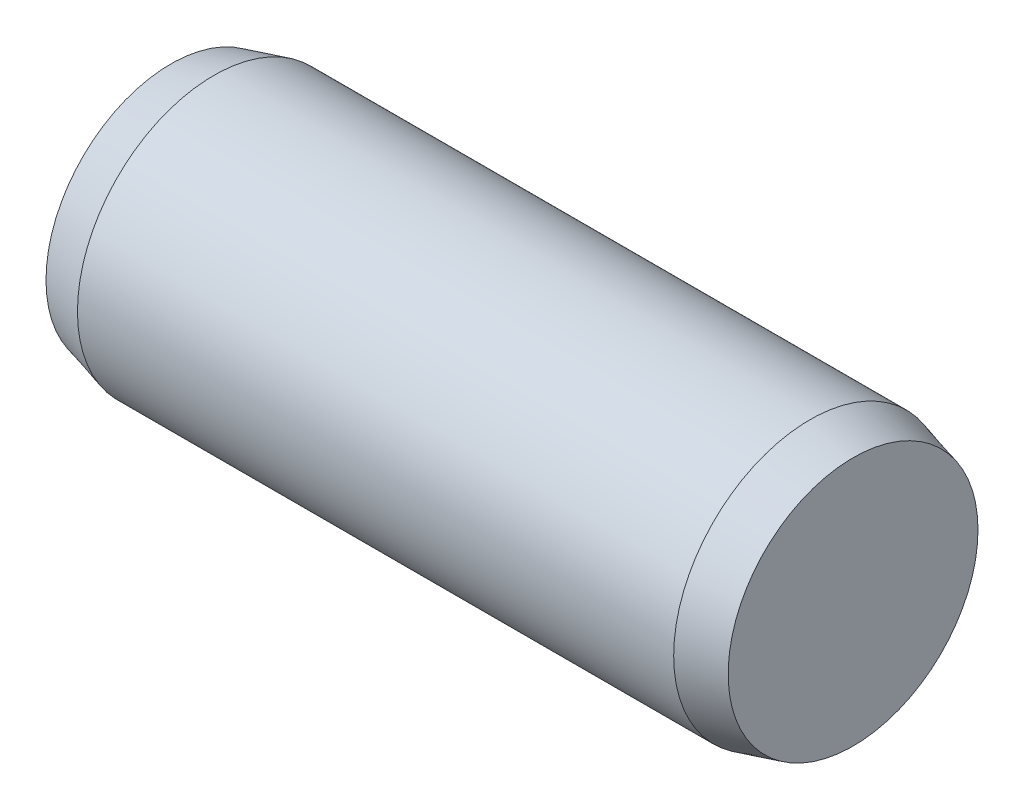
SolidWorks part; units mm, degrees
material "Stainless Steel (ferritic)"
ref_plane "Front Plane" through (0, 0, 0) normal (0, 0, 1) x (1, 0, 0)
ref_plane "Top Plane" through (0, 0, 0) normal (0, 1, 0) x (1, 0, 0)
ref_plane "Right Plane" through (0, 0, 0) normal (1, 0, 0) x (0, 0, -1)
sketch "Sketch1" plane through (0, 0, 0) normal (0, 0, 1) x (1, 0, 0)
  line L0 (-4.37, 0) -> (4.37, 0) construction
  line L1 (4.37, 2) -> (4.37, -2) construction
  line L2 (-4.37, 2) -> (-4.37, -2) construction
  line L3 (5, 2) -> (5, -2) construction
  line L4 (-5, 2) -> (-5, -2) construction
  line L5 (-4.37, 0) -> (-5, 0) construction
  line L6 (4.37, 0) -> (5, 0) construction
  dimension "Dia" = 4
  dimension "C" = 0.63
  dimension "D1" = 0.63
  dimension "Length" = 10
sketch "Sketch2" plane through (0, 0, 0) normal (1, 0, 0) x (0, 0, -1)
  circle A0 centre (0, 0) radius 2
extrude "Extrude1" add sketch "Sketch2" against normal up to vertex (4.37 mm away) and the other way up to vertex (4.37 mm away) up to point (-4.37, 2, 0) other way up to point (4.37, 2, 0)
sketch "Sketch3" plane through (4.37, 0, 0) normal (1, 0, 0) x (0, 0, -1)
  circle A1 centre (0, 0) radius 2
  circle A2 centre (0, 0) radius 2
  dimension "D1" = 0
extrude "Extrude2" add sketch "Sketch3" along normal up to vertex (0.63 mm away) draft 15 up to point (5, 0, 0)
sketch "Sketch4" plane through (-4.37, 0, 0) normal (-1, 0, 0) x (0, 0, 1)
  circle A1 centre (0, 0) radius 2
  circle A2 centre (0, 0) radius 2
  dimension "D1" = 0
extrude "Extrude3" add sketch "Sketch4" along normal up to vertex (0.63 mm away) draft 15 up to point (-5, 0, 0)
equation "\"D1@Sketch1\" = \"C@Sketch1\""
